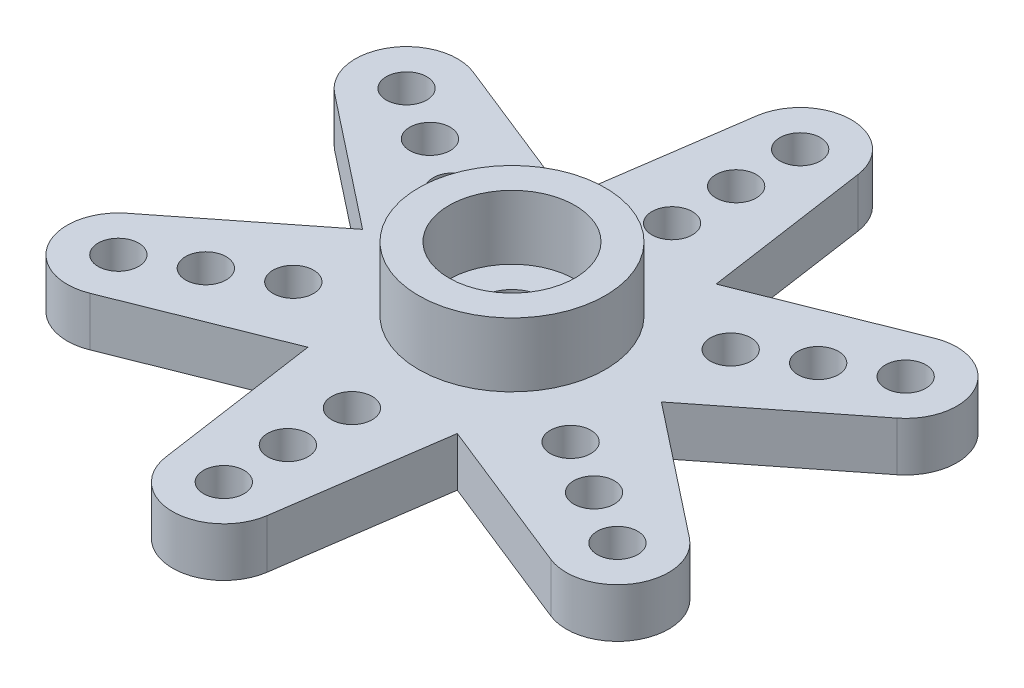
SolidWorks part; units mm, degrees
ref_plane "Alzado" through (0, 0, 0) normal (0, 0, 1) x (1, 0, 0)
ref_plane "Planta" through (0, 0, 0) normal (0, 1, 0) x (1, 0, 0)
ref_plane "Vista lateral" through (0, 0, 0) normal (1, 0, 0) x (0, 0, -1)
sketch "Croquis1" plane through (0, 0, 0) normal (0, 1, 0) x (1, 0, 0)
  line L0 (0, 0) -> (0, 13.5) construction
  line L1 (0, 0) -> (-3.5, 6.0622) construction
  line L2 (-3.5, 6.0622) -> (-2.3753, 13.8433)
  line L3 (3.5, 6.0622) -> (2.3753, 13.8433)
  line L4 (0, 0) -> (3.5, 6.0622) construction
  line L5 (7, 0) -> (13.1763, 4.8646)
  line L6 (3.5, 6.0622) -> (10.801, 8.9787)
  line L7 (3.5, -6.0622) -> (10.801, -8.9787)
  line L8 (7, 0) -> (13.1763, -4.8646)
  line L9 (-3.5, -6.0622) -> (-2.3753, -13.8433)
  line L10 (3.5, -6.0622) -> (2.3753, -13.8433)
  line L11 (-7, 0) -> (-13.1763, -4.8646)
  line L12 (-3.5, -6.0622) -> (-10.801, -8.9787)
  line L13 (-3.5, 6.0622) -> (-10.801, 8.9787)
  line L14 (-7, 0) -> (-13.1763, 4.8646)
  circle A0 centre (0, 0) radius 7 construction
  arc A2 (2.3753, 13.8433) -> (-2.3753, 13.8433) centre (0, 13.5) ccw
  circle A3 centre (0, 13.5) radius 0.95
  circle A4 centre (0, 10.5) radius 0.95
  circle A5 centre (0, 7.5) radius 0.95
  arc A6 (13.1763, 4.8646) -> (10.801, 8.9787) centre (11.6913, 6.75) ccw
  circle A7 centre (11.6913, 6.75) radius 0.95
  circle A8 centre (9.0933, 5.25) radius 0.95
  circle A9 centre (6.4952, 3.75) radius 0.95
  arc A10 (10.801, -8.9787) -> (13.1763, -4.8646) centre (11.6913, -6.75) ccw
  circle A11 centre (11.6913, -6.75) radius 0.95
  circle A12 centre (9.0933, -5.25) radius 0.95
  circle A13 centre (6.4952, -3.75) radius 0.95
  arc A14 (-2.3753, -13.8433) -> (2.3753, -13.8433) centre (0, -13.5) ccw
  circle A15 centre (0, -13.5) radius 0.95
  circle A16 centre (0, -10.5) radius 0.95
  circle A17 centre (0, -7.5) radius 0.95
  arc A18 (-13.1763, -4.8646) -> (-10.801, -8.9787) centre (-11.6913, -6.75) ccw
  circle A19 centre (-11.6913, -6.75) radius 0.95
  circle A20 centre (-9.0933, -5.25) radius 0.95
  circle A21 centre (-6.4952, -3.75) radius 0.95
  arc A22 (-10.801, 8.9787) -> (-13.1763, 4.8646) centre (-11.6913, 6.75) ccw
  circle A23 centre (-11.6913, 6.75) radius 0.95
  circle A24 centre (-9.0933, 5.25) radius 0.95
  circle A25 centre (-6.4952, 3.75) radius 0.95
  circle A26 centre (0, 0) radius 1.5
  point P66 (0, 0)
  dimension "D2" = 14
  dimension "D3" = 4.8
  dimension "D5" = 1.9
  dimension "D9" = 3
  dimension "D1" = 13.5
  dimension "D4" = 30
  dimension "D6" = 3
  dimension "D7" = 3
  dimension "D8" = 6
extrude "Saliente-Extruir1" add sketch "Croquis1" along normal blind 2.3 contours L13 A22 L14 L11 A18 L12 L9 A14 L10 L7 A10 L8 L5 A6 L6 L3 A3 L2 A26 A25 A24 A23 A4 A5 A7 A8 A9 A11 A12 A13 A15 A16 A17
sketch "Croquis2" plane through (0, 2.3, 0) normal (0, 1, 0) x (1, 0, 0)
  circle A0 centre (0, 0) radius 4.375
  circle A1 centre (0, 0) radius 2.95
  dimension "D1" = 8.75
  dimension "D2" = 5.9
extrude "Saliente-Extruir2" add sketch "Croquis2" along normal blind 3
